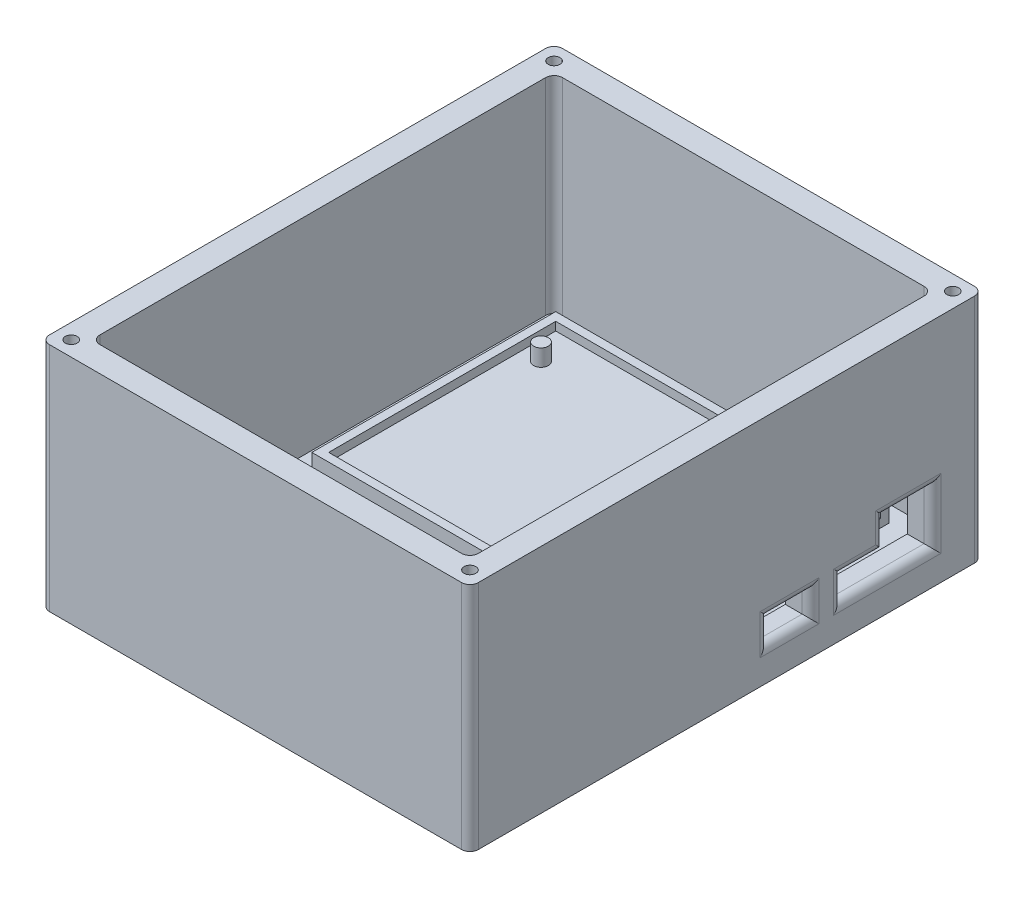
SolidWorks part; units mm, degrees
ref_plane "Front Plane" through (0, 0, 0) normal (0, 0, 1) x (1, 0, 0)
ref_plane "Top Plane" through (0, 0, 0) normal (0, 1, 0) x (1, 0, 0)
ref_plane "Right Plane" through (0, 0, 0) normal (1, 0, 0) x (0, 0, -1)
sketch "Sketch1" plane through (0, 0, 0) normal (0, 1, 0) x (1, 0, 0)
  line L1 (-90, 110) -> (0, 110)
  line L2 (-90, 110) -> (-90, 0)
  line L3 (-90, 0) -> (0, 0)
  line L4 (0, 110) -> (0, 0)
  dimension "D1" = 110
  dimension "D2" = 90
extrude "Boss-Extrude2" add sketch "Sketch1" along normal blind 6
sketch "Sketch4" plane through (0, 0, 0) normal (0, -1, 0) x (1, 0, 0)
  line L0 (-90, -110) -> (-90, 0) construction
  line L1 (-96, 6) -> (6, 6)
  line L2 (-96, 6) -> (-96, -116)
  line L3 (-96, -116) -> (6, -116)
  line L4 (6, 6) -> (6, -116)
  line L5 (0, 0) -> (0, -110) construction
  line L6 (-90, 0) -> (0, 0) construction
  line L7 (0, -110) -> (-90, -110) construction
  line L12 (-90, 0) -> (-90, -110)
  line L13 (-90, -110) -> (0, -110)
  line L14 (0, -110) -> (0, 0)
  line L15 (0, 0) -> (-90, 0)
  line L16 (-90, 0) -> (-90, -110)
  line L17 (-90, -110) -> (0, -110)
  line L18 (0, -110) -> (0, 0)
  line L19 (0, 0) -> (-90, 0)
  dimension "D1" = 6
  dimension "D2" = 6
  dimension "D3" = 6
  dimension "D4" = 6
  dimension "D5" = 0
extrude "Boss-Extrude3" add sketch "Sketch4" against normal blind 55
sketch "Sketch6" plane through (0, 6, 0) normal (0, 1, 0) x (1, 0, 0)
  line L0 (-90, 110) -> (-90, 0) construction
  line L1 (-83.6, 104) -> (-6.4, 104)
  line L2 (-83.6, 104) -> (-83.6, 50)
  line L3 (-83.6, 50) -> (-6.4, 50)
  line L4 (-6.4, 104) -> (-6.4, 50)
  line L6 (0, 110) -> (-90, 110) construction
  line L8 (-85.6, 106) -> (-4.4, 106)
  line L9 (-85.6, 106) -> (-85.6, 48)
  line L10 (-85.6, 48) -> (-4.4, 48)
  line L11 (-4.4, 106) -> (-4.4, 48)
  dimension "D1" = 77.2
  dimension "D2" = 6.4
  dimension "D3" = 6
  dimension "D4" = 2
  dimension "D5" = 2
  dimension "D6" = 54
  dimension "D7" = 2
  dimension "D8" = 2
extrude "Boss-Extrude4" add sketch "Sketch6" along normal blind 4
sketch "Sketch10" plane through (6, 0, 0) normal (1, 0, 0) x (0, 0, -1)
  line L0 (116, 55) -> (116, 0) construction
  line L1 (-6, 0) -> (116, 0)
  line L2 (-6, 0) -> (-6, 8)
  line L3 (-6, 8) -> (116, 8)
  line L4 (116, 0) -> (116, 8)
  line L6 (116, 55) -> (104, 55)
  line L7 (116, 55) -> (116, 0)
  line L8 (116, 0) -> (104, 0)
  line L9 (104, 55) -> (104, 0)
  line L10 (92.5, 20.5) -> (104, 20.5)
  line L11 (92.5, 20.5) -> (92.5, 8)
  line L12 (92.5, 8) -> (104, 8)
  line L13 (104, 20.5) -> (104, 8)
  line L14 (92.5, 13.5) -> (82.5, 13.5)
  line L15 (92.5, 13.5) -> (92.5, 8)
  line L16 (92.5, 8) -> (82.5, 8)
  line L17 (82.5, 13.5) -> (82.5, 8)
  line L18 (82.5, 8) -> (75, 8)
  line L19 (82.5, 8) -> (82.5, 11.2417)
  line L20 (82.5, 11.2417) -> (75, 11.2417)
  line L21 (75, 8) -> (75, 11.2417)
  line L22 (75, 8) -> (65, 8)
  line L23 (75, 8) -> (75, 13.5)
  line L24 (75, 13.5) -> (65, 13.5)
  line L25 (65, 8) -> (65, 13.5)
  dimension "D1" = 8
  dimension "D2" = 12
  dimension "D3" = 11.5
  dimension "D4" = 12.5
  dimension "D5" = 5.5
  dimension "D6" = 10
  dimension "D7" = 7.5
  dimension "D8" = 10
sketch "Sketch11" plane through (0, 10, 0) normal (0, 1, 0) x (1, 0, 0)
  line L0 (-6.4, 104) -> (-6.4, 106)
  line L1 (-6.4, 50) -> (-6.4, 48)
  line L4 (-85.6, 106) -> (-85.6, 48)
  line L5 (-85.6, 48) -> (-4.4, 48)
  line L6 (-4.4, 48) -> (-4.4, 106)
  line L7 (-4.4, 106) -> (-85.6, 106)
  line L8 (-85.6, 106) -> (-85.6, 48)
  line L9 (-85.6, 48) -> (-4.4, 48)
  line L10 (-4.4, 48) -> (-4.4, 106)
  line L11 (-4.4, 106) -> (-85.6, 106)
  line M6 (-85.6, 48) -> (-4.4, 48)
  line M7 (-4.4, 48) -> (-4.4, 106)
  line M8 (-4.4, 106) -> (-85.6, 106)
  line M12 (-6.4, 104) -> (-6.4, 50)
  dimension "D1" = 0
extrude "Cut-Extrude1" cut sketch "Sketch11" against normal blind 4 contours L1 L0 M12 M6 M7 M8
sketch "Sketch12" plane through (0, 6, 0) normal (0, 1, 0) x (1, 0, 0)
  line L0 (-83.6, 50) -> (-6.4, 50) construction
  line L1 (-83.6, 104) -> (-6.4, 104)
  line L2 (-83.6, 104) -> (-83.6, 50)
  line L3 (-83.6, 50) -> (-6.4, 50)
  line L4 (-6.4, 104) -> (-6.4, 50)
extrude "Boss-Extrude5" add sketch "Sketch12" along normal blind 2
extrude "Cut-Extrude2" cut sketch "Sketch10" against normal up to next contours L10 L11 L3 L9 | L14 L17 L3 L11 | L25 L3 L21 L23 L24
fillet "Fillet1" radius 2 10 edges at (6, 10.75, -82.5) (6, 8, -93.25) (6, 14.25, -104) (6, 20.5, -98.25) (6, 17, -92.5) (6, 13.5, -87.5) (6, 10.75, -75) (6, 8, -70) (6, 10.75, -65) (6, 13.5, -70)
fillet "Fillet2" radius 2 4 edges at (-96, 27.5, 6) (-96, 27.5, -116) (6, 27.5, -116) (6, 27.5, 6)
fillet "Fillet3" radius 2 4 edges at (0, 30.5, 0) (-90, 30.5, 0) (0, 30.5, -110) (-90, 30.5, -110)
sketch "Sketch13" plane through (0, 8, 0) normal (0, 1, 0) x (1, 0, 0)
  line L1 (-81.6, 103.5) -> (-4.1, 103.5)
  line L2 (-81.6, 103.5) -> (-81.6, 50.5)
  line L3 (-81.6, 50.5) -> (-4.1, 50.5)
  line L4 (-4.1, 103.5) -> (-4.1, 50.5)
  line L5 (-83.6, 104) -> (-83.6, 50) construction
  line L7 (-83.6, 50) -> (-6.4, 50) construction
  line L9 (-4.1, 50.5) -> (-18.6, 50.5)
  line L10 (-4.1, 50.5) -> (-4.1, 54)
  line L11 (-4.1, 54) -> (-18.6, 54)
  line L12 (-18.6, 50.5) -> (-18.6, 54)
  line L13 (-81.6, 103.5) -> (-79.1, 103.5)
  line L14 (-81.6, 103.5) -> (-81.6, 96)
  line L15 (-81.6, 96) -> (-79.1, 96)
  line L16 (-79.1, 103.5) -> (-79.1, 96)
  circle A0 centre (-18.6, 54) radius 1.75
  circle A1 centre (-79.1, 96) radius 1.75
  dimension "D7" = 3.5
  dimension "D10" = 3.5
  dimension "D1" = 77.5
  dimension "D2" = 53
  dimension "D3" = 0.5
  dimension "D4" = 2
  dimension "D5" = 14.5
  dimension "D6" = 3.5
  dimension "D8" = 2.5
  dimension "D9" = 7.5
extrude "Boss-Extrude7" add sketch "Sketch13" along normal blind 4 contours L16 A1 L15 | L15 A1 L16 | L11 A0 L12 | L12 A0 L11
sketch "Sketch14" plane through (0, 55, 0) normal (0, 1, 0) x (1, 0, 0)
  line L0 (-95.4142, 115.4142) -> (-89.4142, 109.4142) construction
  arc A0 (-94, 116) -> (-96, 114) centre (-94, 114) ccw construction
  arc A1 (-88, 110) -> (-90, 108) centre (-88, 108) ccw construction
  circle A2 centre (-92.4142, 112.4142) radius 1.4
  dimension "D1" = 2.8
extrude "Cut-Extrude3" cut sketch "Sketch14" against normal blind 8
ref_plane "Plane1" through (-45, 0, 0) normal (-1, 0, 0) x (0, 0, 1)
mirror "Mirror1" about plane through (-45, 0, 0) normal (-1, 0, 0) of "Cut-Extrude3"
ref_plane "Plane2" through (0, 0, -55) normal (0, 0, -1) x (-1, 0, 0)
mirror "Mirror2" about plane through (0, 0, -55) normal (0, 0, -1) of "Mirror1", "Cut-Extrude3"
